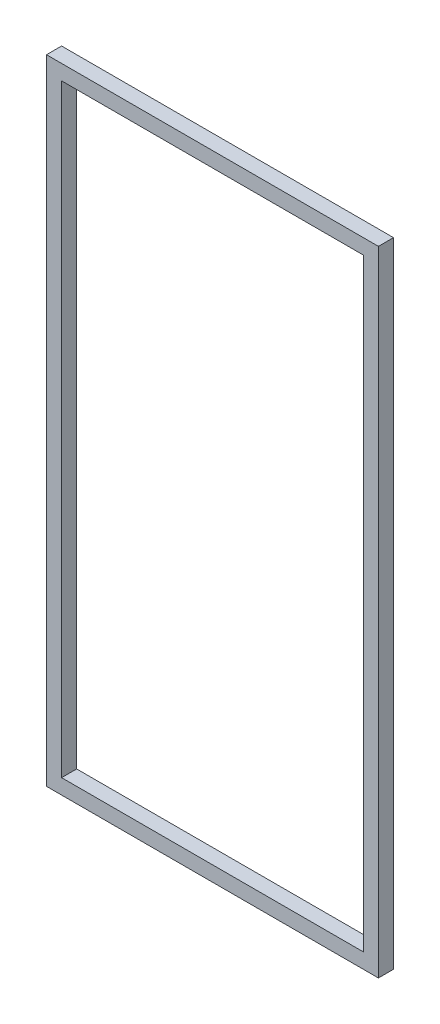
SolidWorks part; units mm, degrees
ref_plane "Front Plane" through (0, 0, 0) normal (0, 0, 1) x (1, 0, 0)
ref_plane "Top Plane" through (0, 0, 0) normal (0, 1, 0) x (1, 0, 0)
ref_plane "Right Plane" through (0, 0, 0) normal (1, 0, 0) x (0, 0, -1)
sketch "Sketch1" plane through (0, 0, 0) normal (0, 0, 1) x (1, 0, 0)
  line L1 (550, -1050) -> (-550, -1050)
  line L2 (550, -1050) -> (550, 1050)
  line L3 (550, 1050) -> (-550, 1050)
  line L4 (-550, -1050) -> (-550, 1050)
  line L5 (550, -1050) -> (-550, 1050) construction
  line L6 (550, 1050) -> (-550, -1050) construction
  point P0 (0, 0)
  dimension "D1" = 2100
  dimension "D2" = 1100
extrude "Boss-Extrude1" add sketch "Sketch1" along normal blind 50
sketch "Sketch2" plane through (0, 0, 50) normal (0, 0, 1) x (1, 0, 0)
  line L0 (-550, -1050) -> (550, -1050) construction
  line L1 (500, -1000) -> (-500, -1000)
  line L2 (500, -1000) -> (500, 1000)
  line L3 (500, 1000) -> (-500, 1000)
  line L4 (-500, -1000) -> (-500, 1000)
  line L5 (500, -1000) -> (-500, 1000) construction
  line L6 (500, 1000) -> (-500, -1000) construction
  point P0 (0, 0)
  dimension "D1" = 1000
  dimension "D2" = 2000
  dimension "D3" = 50
extrude "Cut-Extrude1" cut sketch "Sketch2" against normal blind 50
